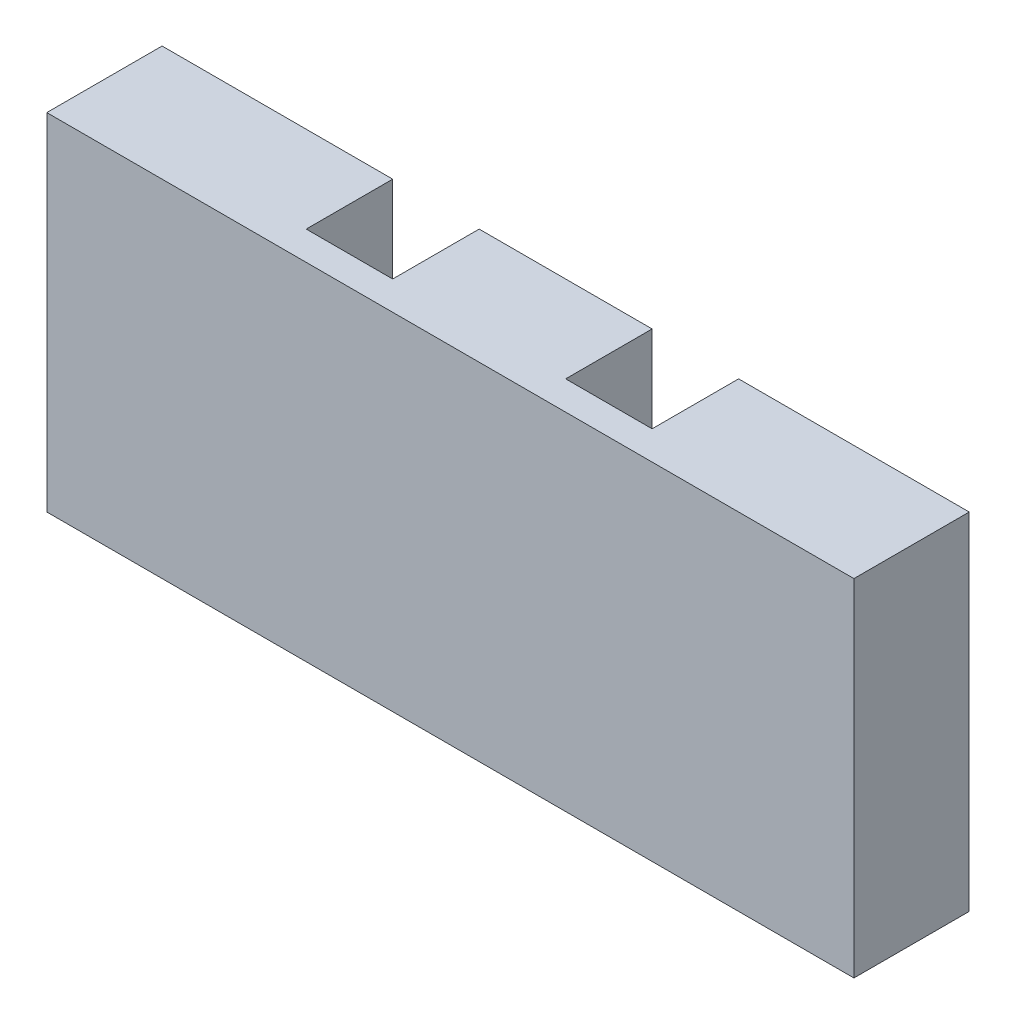
SolidWorks part; units mm, degrees
ref_plane "정면" through (0, 0, 0) normal (0, 0, 1) x (1, 0, 0)
ref_plane "윗면" through (0, 0, 0) normal (0, 1, 0) x (1, 0, 0)
ref_plane "우측면" through (0, 0, 0) normal (1, 0, 0) x (0, 0, -1)
sketch "스케치1" plane through (0, 0, 0) normal (0, 0, 1) x (1, 0, 0)
  line L1 (-140, 60) -> (140, 60)
  line L2 (-140, 60) -> (-140, -60)
  line L3 (-140, -60) -> (140, -60)
  line L4 (140, 60) -> (140, -60)
  line L5 (-140, 60) -> (140, -60) construction
  line L6 (-140, -60) -> (140, 60) construction
  point P0 (0, 0)
  dimension "D1" = 120
  dimension "D2" = 280
extrude "보스-돌출1" add sketch "스케치1" along normal blind 10
sketch "스케치2" plane through (0, 0, 0) normal (0, 0, -1) x (-1, 0, 0)
  line L0 (-140, 60) -> (140, 60) construction
  line L1 (-30, 10) -> (30, 10)
  line L2 (-30, 10) -> (-30, 60)
  line L3 (-30, 60) -> (30, 60)
  line L4 (30, 10) -> (30, 60)
  line L5 (-30, 10) -> (30, 60) construction
  line L6 (-30, 60) -> (30, 10) construction
  point P0 (0, 35)
  dimension "D1" = 60
  dimension "D2" = 50
  dimension "D3" = 0
extrude "보스-돌출2" add sketch "스케치2" along normal blind 30
sketch "스케치3" plane through (0, 0, 0) normal (0, 0, -1) x (-1, 0, 0)
  line L0 (140, -60) -> (-140, -60) construction
  line L1 (-140, 60) -> (-60, 60)
  line L2 (-140, 60) -> (-140, -60)
  line L3 (-140, -60) -> (-60, -60)
  line L4 (-60, 60) -> (-60, -60)
  line L6 (140, 60) -> (60, 60)
  line L7 (140, 60) -> (140, -60)
  line L8 (140, -60) -> (60, -60)
  line L9 (60, 60) -> (60, -60)
  dimension "D1" = 80
  dimension "D2" = 80
extrude "보스-돌출3" add sketch "스케치3" along normal blind 30
